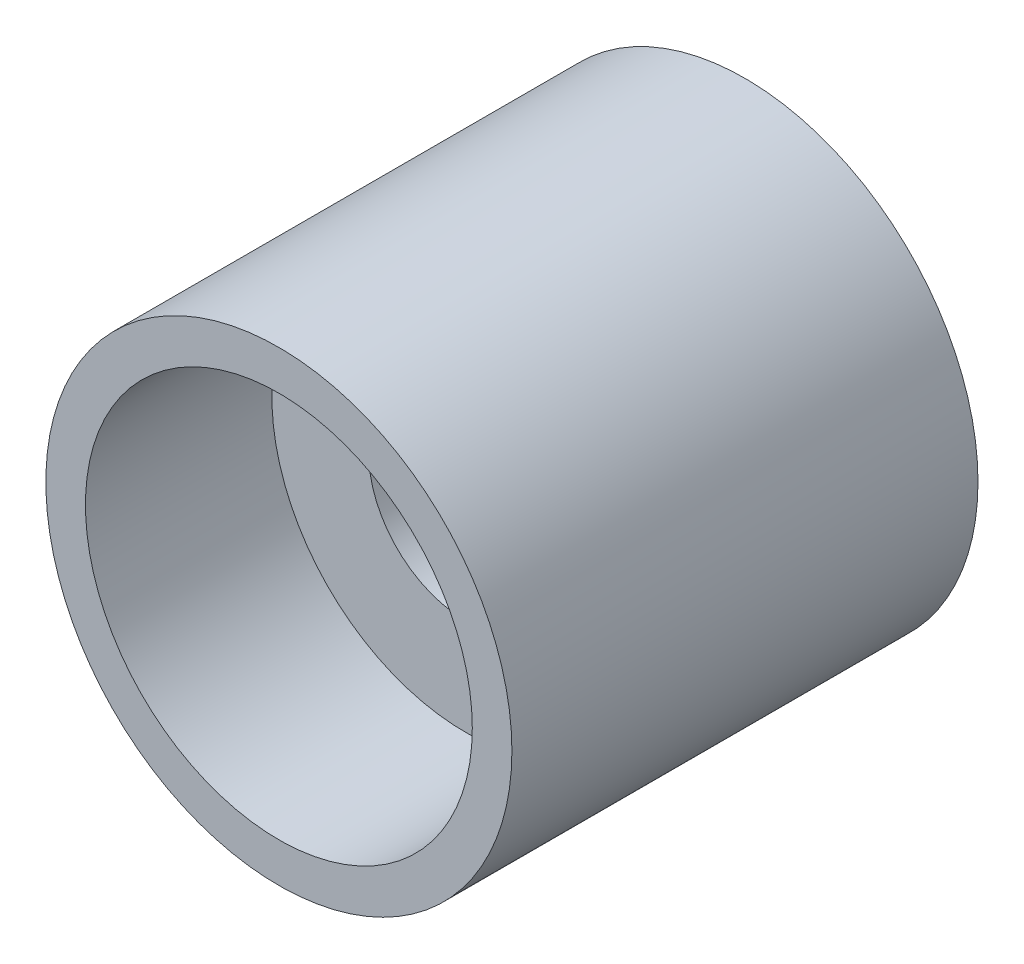
SolidWorks part; units mm, degrees
ref_plane "Front Plane" through (0, 0, 0) normal (0, 0, 1) x (1, 0, 0)
ref_plane "Top Plane" through (0, 0, 0) normal (0, 1, 0) x (1, 0, 0)
ref_plane "Right Plane" through (0, 0, 0) normal (1, 0, 0) x (0, 0, -1)
sketch "Sketch1" plane through (0, 0, 0) normal (0, 0, 1) x (1, 0, 0)
  circle A0 centre (0, 0) radius 10
  circle A1 centre (0, 0) radius 4.15
  dimension "D1" = 20
  dimension "D2" = 8.3
extrude "Boss-Extrude1" add sketch "Sketch1" along normal blind 20
sketch "Sketch2" plane through (0, 0, 20) normal (0, 0, 1) x (1, 0, 0)
  circle A0 centre (0, 0) radius 8.3
  circle A1 centre (0, 0) radius 10 construction
  dimension "D1" = 1.7
extrude "Cut-Extrude1" cut sketch "Sketch2" against normal blind 8
